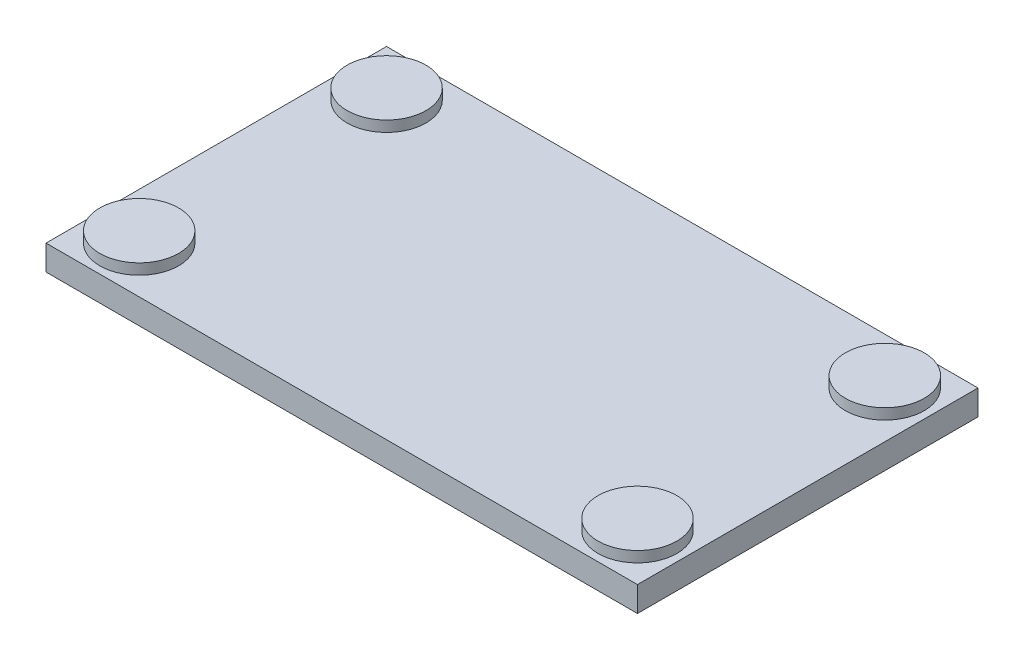
SolidWorks part; units mm, degrees
ref_plane "前视基准面" through (0, 0, 0) normal (0, 0, 1) x (1, 0, 0)
ref_plane "上视基准面" through (0, 0, 0) normal (0, 1, 0) x (1, 0, 0)
ref_plane "右视基准面" through (0, 0, 0) normal (1, 0, 0) x (0, 0, -1)
other "Configuration Table"
sketch "草图1" plane through (0, 0, 0) normal (0, 1, 0) x (1, 0, 0)
  line L1 (-82.5, 47.5) -> (82.5, 47.5)
  line L2 (-82.5, 47.5) -> (-82.5, -47.5)
  line L3 (-82.5, -47.5) -> (82.5, -47.5)
  line L4 (82.5, 47.5) -> (82.5, -47.5)
  line L5 (-82.5, 47.5) -> (82.5, -47.5) construction
  line L6 (-82.5, -47.5) -> (82.5, 47.5) construction
  point P0 (0, 0)
  dimension "D1" = 165
  dimension "D2" = 95
extrude "凸台-拉伸1" add sketch "草图1" along normal blind 7
sketch "草图2" plane through (0, 7, 0) normal (0, 1, 0) x (1, 0, 0)
  line L0 (82.5, 47.5) -> (-82.5, 47.5) construction
  line L1 (82.5, -47.5) -> (82.5, 47.5) construction
  line L2 (0, 0) -> (15.1366, 0)
  line L3 (0, 0) -> (0, 16.5461)
  circle A0 centre (69.5, 34.5) radius 11
  circle A1 centre (69.5, -34.5) radius 11
  circle A2 centre (-69.5, -34.5) radius 11
  circle A3 centre (-69.5, 34.5) radius 11
  dimension "D3" = 22
  dimension "D1" = 13
  dimension "D2" = 13
extrude "凸台-拉伸2" add sketch "草图2" along normal blind 3 contours A3 | A2 | A0 | A1
